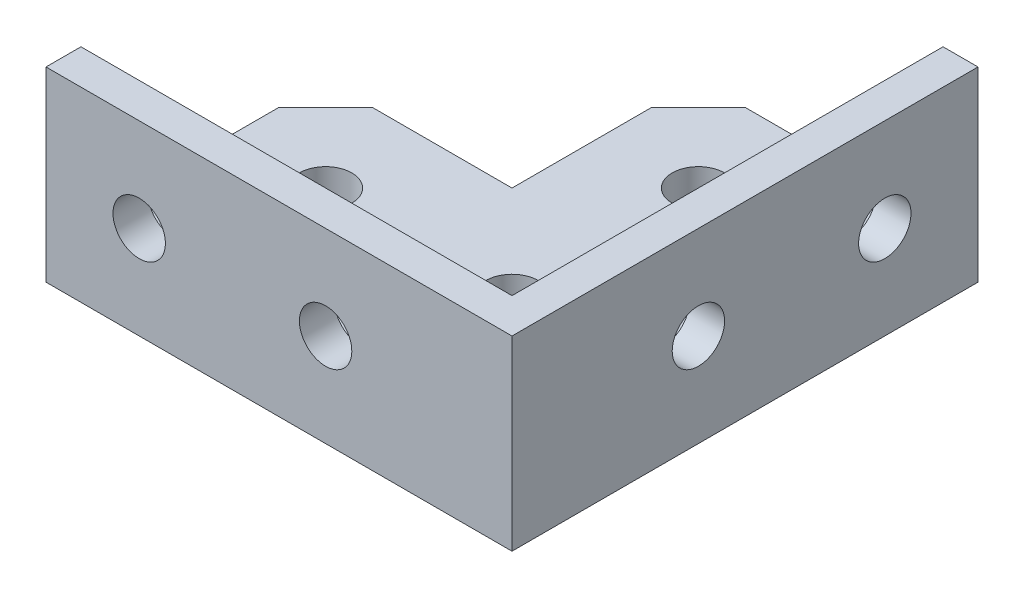
SolidWorks part; units mm, degrees
material "6061 Alloy"
ref_plane "Front Plane" through (0, 0, 0) normal (0, 0, 1) x (1, 0, 0)
ref_plane "Top Plane" through (0, 0, 0) normal (0, 1, 0) x (1, 0, 0)
ref_plane "Right Plane" through (0, 0, 0) normal (1, 0, 0) x (0, 0, -1)
sketch "Sketch1" plane through (0, 0, 0) normal (0, 0, 1) x (1, 0, 0)
  line L0 (0, 0) -> (38.1, 0)
  line L1 (38.1, 0) -> (38.1, 25.4)
  line L2 (38.1, 25.4) -> (33.3375, 25.4)
  line L3 (33.3375, 25.4) -> (33.3375, 4.7625)
  line L4 (33.3375, 4.7625) -> (0, 4.7625)
  line L5 (0, 4.7625) -> (0, 0)
  dimension "D1" = 38.1
  dimension "D2" = 25.4
  dimension "D3" = 4.7625
extrude "Boss-Extrude1" add sketch "Sketch1" along normal blind 63.5 contours L4 L5 L0 L1 L2 L3
sketch "Sketch6" plane through (0, 4.7625, 0) normal (0, 1, 0) x (1, 0, 0)
  line L0 (12.7, -63.5) -> (12.7, 0) construction
  line L1 (33.3375, -63.5) -> (0, -63.5) construction
  line L2 (33.3375, 0) -> (0, 0) construction
  line L6 (12.7, -63.5) -> (12.7, -38.1) construction
  line L7 (0, -63.5) -> (0, 0) construction
  point P8 (12.7, -63.5)
  point P38 (12.7, -38.1)
  point P39 (12.7, -12.7)
  dimension "D1" = 12.7
  dimension "D2" = 12.7
  dimension "D4" = 25.4
  dimension "D3" = 3
hole_wizard "1/4 Clearance Hole1" positions "Sketch6" profile "Sketch7" hole size "1/4" standard "ANSI Inch"
sketch "Sketch7" plane through (12.7, 4.7625, 12.7) normal (1, 0, 0) x (0, 0, 1)
  line L0 (0, 0) -> (0, 4.7625)
  line L1 (0, 4.7625) -> (3.5712, 4.7625)
  line L2 (3.5712, 4.7625) -> (3.5712, 0)
  line L5 (3.5712, 0) -> (0, 0)
  line L11 (0, -6.35) -> (0, 107.95) construction
  dimension "Thru Hole Dia." = 7.1425
  dimension "Thru Hole Depth" = 4.7625
sketch "Sketch8" plane through (33.3375, 0, 0) normal (-1, 0, 0) x (0, 0, 1)
  line L0 (0, 12.7) -> (63.5, 12.7) construction
  line L1 (0, 25.4) -> (0, 4.7625) construction
  line L4 (12.7, 12.7) -> (38.1, 12.7) construction
  line L5 (63.5, 25.4) -> (63.5, 4.7625) construction
  line L6 (63.5, 25.4) -> (0, 25.4) construction
  point P6 (12.7, 12.7)
  point P26 (38.1, 12.7)
  point P35 (0, 0)
  point P36 (0, 0)
  dimension "D1" = 12.7
  dimension "D3" = 25.4
  dimension "D4" = 12.7
  dimension "D2" = 2
hole_wizard "1/4 Clearance Hole2" positions "Sketch8" profile "Sketch9" hole size "1/4" standard "ANSI Inch" end condition up to next
sketch "Sketch9" plane through (33.3375, 12.7, 38.1) normal (0, 1, 0) x (0, 0, 1)
  line L0 (0, 0) -> (0, 4.7625)
  line L1 (0, 4.7625) -> (3.5712, 4.7625)
  line L2 (3.5712, 4.7625) -> (3.5712, 0)
  line L5 (3.5712, 0) -> (0, 0)
  line L11 (0, -6.35) -> (0, 107.95) construction
  dimension "Thru Hole Dia." = 7.1425
  dimension "Thru Hole Depth" = 4.7625
sketch "Sketch10" plane through (0, 4.7625, 0) normal (0, 1, 0) x (1, 0, 0)
  line L0 (12.7, -38.1) -> (35.5941, -60.9941)
  line L1 (33.3375, -63.5) -> (33.3375, 0) construction
  dimension "D1" = 45
sketch "Sketch13" plane through (0, 0, 0) normal (0, 0, -1) x (-1, 0, 0)
  line L0 (-33.3375, 25.4) -> (-12.7, 4.7625)
  line L1 (-33.3375, 25.4) -> (-33.3375, 4.7625) construction
  line L2 (-33.3375, 4.7625) -> (0, 4.7625) construction
  line L3 (-12.7, 4.7625) -> (-33.3375, 4.7625)
  line L4 (-33.3375, 4.7625) -> (-33.3375, 25.4)
extrude "Boss-Extrude2" [suppressed] add sketch "Sketch13" against normal blind 3.175
ref_plane "Plane1" through (-12.7, 0, 12.7) normal (0.7071, 0, -0.7071) x (-0.7071, 0, -0.7071)
mirror "Mirror1" about plane through (-12.7, 0, 12.7) normal (0.7071, 0, -0.7071) of "Boss-Extrude2", "1/4 Clearance Hole1", "1/4 Clearance Hole2", "Boss-Extrude1"
chamfer "Chamfer1" [suppressed] distance 6.35 angle 45
sketch "Sketch15" plane through (0, 4.7625, 0) normal (0, 1, 0) x (1, 0, 0)
chamfer "Chamfer2" [suppressed] distance 12.7 angle 45
chamfer "Chamfer3" [suppressed] distance 3.175 angle 45
chamfer "Chamfer4" distance 6.35 angle 45 2 edges at (-25.4, 2.3813, 25.4) (0, 2.3813, 0)
